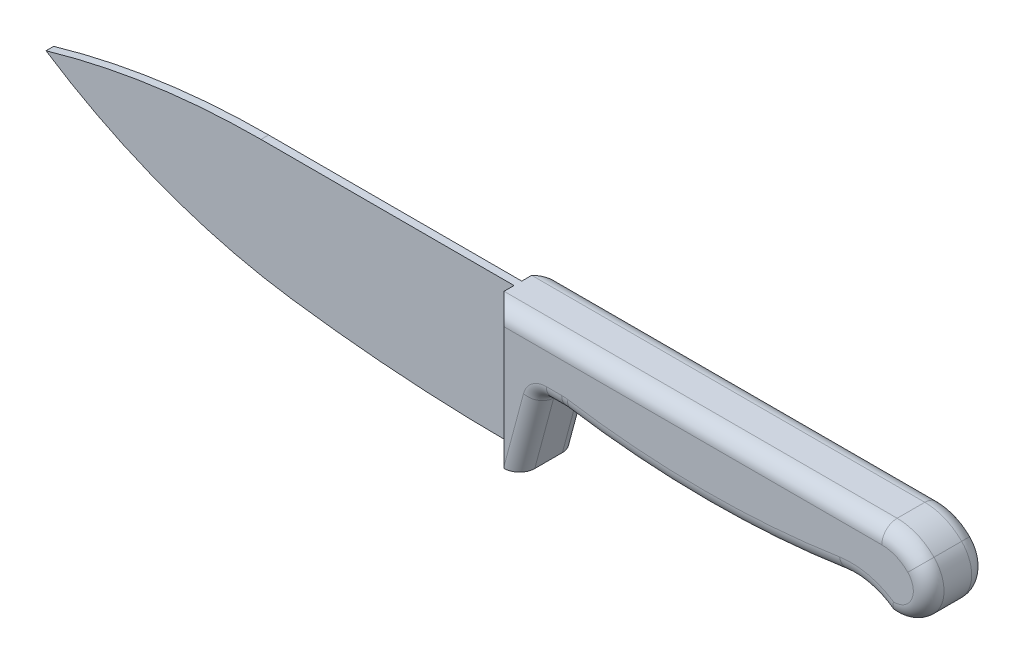
SolidWorks part; units mm, degrees
ref_plane "Front Plane" through (0, 0, 0) normal (0, 0, 1) x (1, 0, 0)
ref_plane "Top Plane" through (0, 0, 0) normal (0, 1, 0) x (1, 0, 0)
ref_plane "Right Plane" through (0, 0, 0) normal (1, 0, 0) x (0, 0, -1)
sketch "Sketch1" plane through (0, 0, 0) normal (0, 0, 1) x (1, 0, 0)
  line L0 (0, 0) -> (0, -45)
  line L1 (40.1015, -45) -> (-49959.8985, -45) construction
  line L2 (-82.4, 0) -> (0, 0)
  arc A0 (-152.4, -10) -> (-72.4, -40) centre (-45.5941, 153.149) ccw
  arc A1 (-72.4, -40) -> (0, -45) centre (0, 481.676) ccw
  arc A2 (-152.4, -10) -> (-82.4, 0) centre (-82.4, -250) cw
  point P3 (-152.4, -10)
  point P8 (-110.4396, -45)
  point P11 (-98.4918, -39.9176)
  point P12 (-83.8834, 0)
  point P13 (-75.7675, -40)
  dimension "D1" = 45
  dimension "D2" = 152.4
  dimension "D3" = 10
  dimension "D4" = 30
  dimension "D5" = 80
  dimension "D6" = 70
extrude "Boss-Extrude1" add sketch "Sketch1" along normal mid plane 2.5
sketch "Sketch2" plane through (0, 0, 0) normal (0, 0, 1) x (1, 0, 0)
  line L0 (0, 0) -> (128, 0)
  line L1 (0, -45) -> (10, -45)
  line L2 (0, -45) -> (0, 0) construction
  line L3 (10, -45) -> (16.1628, -22)
  line L4 (18.7693, -20) -> (23.7693, -20)
  line L5 (0, -45) -> (0, 0)
  arc A0 (16.1628, -22) -> (18.7693, -20) centre (18.7693, -22.6984) cw
  arc A1 (24.9947, -20.0944) -> (114.9947, -20.2271) centre (70.4269, 273.0013) ccw
  arc A2 (114.9947, -20.2271) -> (130, -24) centre (118, -40) cw
  arc A3 (128, 0) -> (140, -5) centre (128, -16.9) cw
  arc A4 (140, -5) -> (130, -24) centre (132.0081, -12.9253) cw
  arc A5 (24.9947, -20.0944) -> (23.7693, -20) centre (23.7693, -28) ccw
  point P18 (0, 0)
  point P21 (130.3425, -23.9493)
  point P22 (0, 0)
  point P24 (132.0458, -23.7448)
  point P25 (131.0763, -24)
  point P26 (129.9753, -24)
  point P27 (140, -2.9825)
  point P36 (118, -20)
  dimension "D7" = 90
  dimension "D9" = 8
  dimension "D10" = 20
  dimension "D1" = 140
  dimension "D2" = 10
  dimension "D3" = 25
  dimension "D4" = 23
  dimension "D5" = 105
  dimension "D6" = 12
  dimension "D8" = 5
  dimension "D11" = 4
  dimension "D12" = 2
  dimension "D13" = 5
extrude "Boss-Extrude2" add sketch "Sketch2" along normal mid plane 19
chamfer "Chamfer1" distance 5 angle 45 2 edges at (0, -22.5, -9.5) (0, -22.5, 9.5)
fillet "Fillet1" radius 5 18 edges at (13.0814, -33.5, -9.5) (17.1266, -20.5576, -9.5) (21.2693, -20, -9.5) (24.3838, -20.0236, -9.5) (122.877, -20.6037, -9.5) (141.9681, -18.1674, -9.5) (134.5, -1.3, -9.5) (13.0814, -33.5, 9.5) (17.1266, -20.5576, 9.5) (21.2693, -20, 9.5) (24.3838, -20.0236, 9.5) (122.877, -20.6037, 9.5) (141.9681, -18.1674, 9.5) (134.5, -1.3, 9.5) (69.9896, -23.5944, -9.5) (66.5, 0, -9.5) (69.9896, -23.5944, 9.5) (66.5, 0, 9.5)
